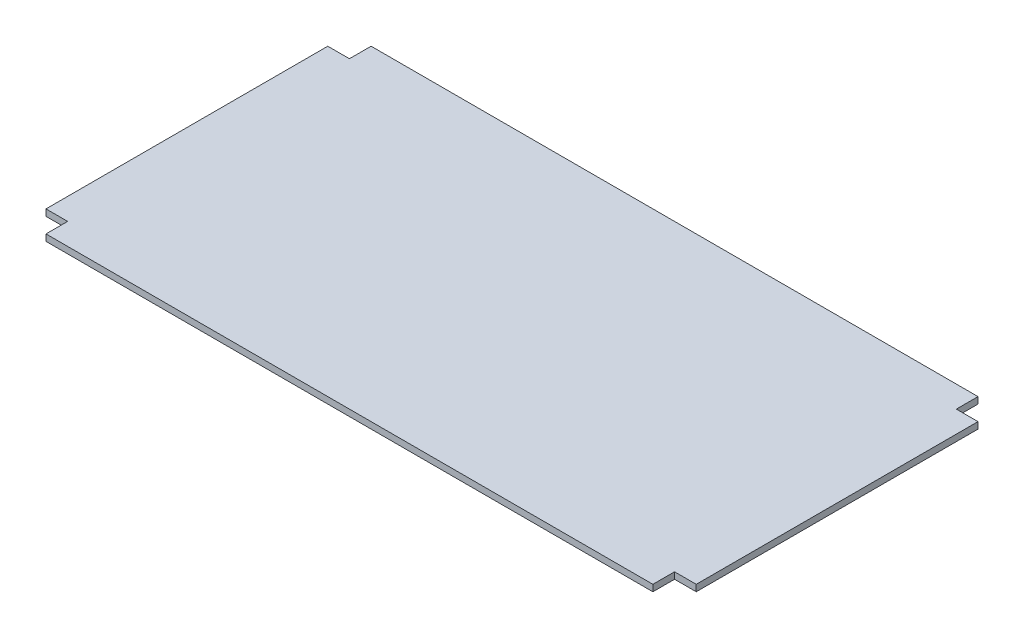
SolidWorks part; units mm, degrees
material "Sosna"
ref_plane "Płaszczyzna przednia" through (0, 0, 0) normal (0, 0, 1) x (1, 0, 0)
ref_plane "Płaszczyzna górna" through (0, 0, 0) normal (0, 1, 0) x (1, 0, 0)
ref_plane "Płaszczyzna prawa" through (0, 0, 0) normal (1, 0, 0) x (0, 0, -1)
sketch "Szkic1" plane through (0, 0, 0) normal (0, 1, 0) x (1, 0, 0)
  line L1 (0, 0) -> (600, 0)
  line L2 (0, 0) -> (0, 300)
  line L3 (0, 300) -> (600, 300)
  line L4 (600, 0) -> (600, 300)
  dimension "D1" = 300
  dimension "D2" = 600
extrude "Dodanie-wyciągnięcie1" add sketch "Szkic1" along normal blind 6
sketch "Szkic2" plane through (0, 6, 0) normal (0, 1, 0) x (1, 0, 0)
  line L0 (580, 0) -> (580, 20)
  line L1 (0, 0) -> (20, 0)
  line L2 (0, 0) -> (0, 20)
  line L3 (0, 20) -> (20, 20)
  line L4 (20, 0) -> (20, 20)
  line L5 (580, 0) -> (600, 0)
  line L6 (600, 0) -> (600, 20)
  line L7 (580, 20) -> (600, 20)
  line L8 (580, 280) -> (580, 300)
  line L9 (580, 280) -> (600, 280)
  line L10 (600, 280) -> (600, 300)
  line L11 (580, 300) -> (600, 300)
  line L12 (0, 280) -> (0, 300)
  line L13 (0, 280) -> (20, 280)
  line L14 (20, 280) -> (20, 300)
  line L15 (0, 300) -> (20, 300)
  dimension "D1" = 20
  dimension "D2" = 20
  dimension "D3" = 2
  dimension "D4" = 2
extrude "Wytnij-wyciągnięcie1" cut sketch "Szkic2" against normal through all
